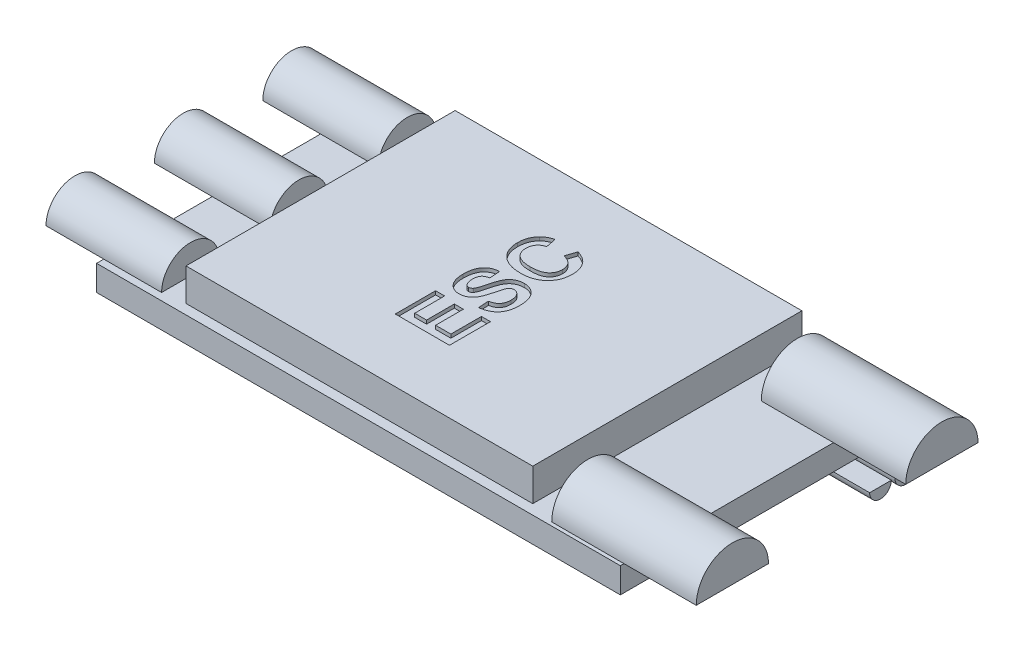
SolidWorks part; units mm, degrees
ref_plane "Front Plane" through (0, 0, 0) normal (0, 0, 1) x (1, 0, 0)
ref_plane "Top Plane" through (0, 0, 0) normal (0, 1, 0) x (1, 0, 0)
ref_plane "Right Plane" through (0, 0, 0) normal (1, 0, 0) x (0, 0, -1)
sketch "Sketch1" plane through (0, 0, 0) normal (0, 1, 0) x (1, 0, 0)
  line L1 (-14.5, 8) -> (14.5, 8)
  line L2 (-14.5, 8) -> (-14.5, -8)
  line L3 (-14.5, -8) -> (14.5, -8)
  line L4 (14.5, 8) -> (14.5, -8)
  line L5 (-14.5, 8) -> (14.5, -8) construction
  line L6 (-14.5, -8) -> (14.5, 8) construction
  point P0 (0, 0)
  dimension "D1" = 29
  dimension "D2" = 16
extrude "Boss-Extrude1" add sketch "Sketch1" along normal mid plane 1.4
sketch "Sketch2" plane through (0, 0.7, 0) normal (0, 1, 0) x (1, 0, 0)
  line L0 (-14.5, 0) -> (14.5, 0) construction
  line L1 (-14.5, 8) -> (-14.5, -8) construction
  line L2 (14.5, -8) -> (14.5, 8) construction
  line L4 (-10.1, 7.45) -> (9.1, 7.45)
  line L5 (-10.1, 7.45) -> (-10.1, -7.45)
  line L6 (-10.1, -7.45) -> (9.1, -7.45)
  line L7 (9.1, 7.45) -> (9.1, -7.45)
  line L8 (-10.1, 7.45) -> (9.1, -7.45) construction
  line L9 (-10.1, -7.45) -> (9.1, 7.45) construction
  point P6 (-0.5, 0)
  dimension "D1" = 14.9
  dimension "D2" = 19.2
  dimension "D3" = 5.4
extrude "Boss-Extrude2" add sketch "Sketch2" along normal blind 1.8
sketch "Sketch3" plane through (0, 0.7, 0) normal (0, 1, 0) x (1, 0, 0)
  line L0 (14.5, -5.8) -> (10.5, -5.8) construction
  line L1 (10.5, -3.8) -> (18.5, -3.8)
  line L2 (10.5, -3.8) -> (10.5, -7.8)
  line L3 (10.5, -7.8) -> (18.5, -7.8)
  line L4 (14.5, -8) -> (14.5, 8)
  line L5 (14.5, 8) -> (-14.5, 8)
  line L6 (-14.5, 8) -> (-14.5, -8)
  line L7 (-14.5, -8) -> (14.5, -8)
  line L8 (14.5, -8) -> (14.5, 8) construction
  line L9 (14.5, 8) -> (-14.5, 8) construction
  line L10 (-14.5, 8) -> (-14.5, -8) construction
  line L11 (-14.5, -8) -> (14.5, -8) construction
  line L12 (18.5, -3.8) -> (18.5, -7.8)
  line L13 (10.5, -3.8) -> (18.5, -7.8) construction
  line L14 (10.5, -7.8) -> (18.5, -3.8) construction
  line L15 (10.5, -5.8) -> (18.5, -5.8)
  point P2 (14.5, -5.8)
  dimension "D2" = 4
  dimension "D3" = 4
  dimension "D4" = 0.2
  dimension "D1" = 0
revolve "Revolve1" add sketch "Sketch3" angle 180 about L15
sketch "Sketch4" plane through (0, 0.7, 0) normal (0, 1, 0) x (1, 0, 0)
  line L0 (-17.7, 0) -> (-11.3, 0)
  line L1 (-17.7, 1.6) -> (-11.3, 1.6)
  line L2 (-17.7, 1.6) -> (-17.7, -1.6)
  line L3 (-17.7, -1.6) -> (-11.3, -1.6)
  line L4 (-11.3, 1.6) -> (-11.3, -1.6)
  line L5 (-17.7, 1.6) -> (-11.3, -1.6) construction
  line L6 (-17.7, -1.6) -> (-11.3, 1.6) construction
  line L13 (14.5, -3.8) -> (14.5, 8)
  line L14 (14.5, 8) -> (-14.5, 8)
  line L15 (-14.5, 8) -> (-14.5, -8)
  line L16 (-14.5, -8) -> (14.5, -8)
  line L17 (14.5, -8) -> (14.5, -7.8)
  line L18 (14.5, -7.8) -> (10.5, -7.8)
  line L19 (10.5, -7.8) -> (10.5, -3.8)
  line L20 (10.5, -3.8) -> (14.5, -3.8)
  line L25 (14.5, -3.8) -> (14.5, 8) construction
  line L26 (14.5, 8) -> (-14.5, 8) construction
  line L27 (-14.5, 8) -> (-14.5, -8) construction
  line L28 (-14.5, -8) -> (14.5, -8) construction
  line L29 (14.5, -8) -> (14.5, -7.8) construction
  line L30 (14.5, -7.8) -> (10.5, -7.8) construction
  line L31 (10.5, -7.8) -> (10.5, -3.8) construction
  line L32 (10.5, -3.8) -> (14.5, -3.8) construction
  point P2 (-14.5, 0)
  dimension "D2" = 3.2
  dimension "D3" = 3.2
  dimension "D1" = 0
revolve "Revolve2" add sketch "Sketch4" angle 180 about L0
sketch "Sketch5" plane through (0, 0.7, 0) normal (0, 1, 0) x (1, 0, 0)
  line L0 (-17.7, 0) -> (-11.3, 0) construction
  line L1 (-17.7, 0) -> (-11.3, 0) construction
  line L2 (-14.5, -1.6) -> (-14.5, -8) construction
  line L3 (-17.7, -4.4) -> (-11.3, -4.4)
  line L4 (-11.3, 1.6) -> (-17.7, 1.6)
  line L5 (-11.3, -1.6) -> (-11.3, 1.6)
  line L6 (-17.7, -1.6) -> (-11.3, -1.6)
  line L7 (-17.7, 1.6) -> (-17.7, -1.6)
  line L8 (-11.3, 1.6) -> (-17.7, 1.6) construction
  line L9 (-11.3, -1.6) -> (-11.3, 1.6) construction
  line L10 (-17.7, -1.6) -> (-11.3, -1.6) construction
  line L11 (-17.7, 1.6) -> (-17.7, -1.6) construction
  line L12 (-17.7, -4.4) -> (-17.7, -7.6)
  line L13 (-17.7, -7.6) -> (-11.3, -7.6)
  line L14 (-11.3, -4.4) -> (-11.3, -7.6)
  line L15 (-17.7, -4.4) -> (-11.3, -7.6) construction
  line L16 (-17.7, -7.6) -> (-11.3, -4.4) construction
  line L17 (-14.5, -8) -> (14.5, -8) construction
  line L18 (-17.7, -6) -> (-11.3, -6)
  point P6 (-14.5, -6)
  dimension "D2" = 3.2
  dimension "D3" = 3.2
  dimension "D4" = 0.4
  dimension "D1" = 0
revolve "Revolve3" add sketch "Sketch5" angle 180 about L18
mirror "Mirror1" about plane through (0, 0, 0) normal (0, 0, 1) of "Revolve3", "Revolve1"
sketch "Sketch6" plane through (0, -0.7, 0) normal (0, -1, 0) x (1, 0, 0)
  line L0 (12.5, -7.2) -> (16.5, -7.2)
  line L1 (12.5, -6.6) -> (16.5, -6.6)
  line L2 (12.5, -6.6) -> (12.5, -7.8)
  line L3 (12.5, -7.8) -> (16.5, -7.8)
  line L4 (14.5, -8) -> (14.5, 8)
  line L5 (14.5, 8) -> (-14.5, 8)
  line L6 (-14.5, 8) -> (-14.5, -8)
  line L7 (-14.5, -8) -> (14.5, -8)
  line L8 (14.5, -8) -> (14.5, 8) construction
  line L9 (14.5, 8) -> (-14.5, 8) construction
  line L10 (-14.5, 8) -> (-14.5, -8) construction
  line L11 (-14.5, -8) -> (14.5, -8) construction
  line L12 (16.5, -6.6) -> (16.5, -7.8)
  line L13 (12.5, -6.6) -> (16.5, -7.8) construction
  line L14 (12.5, -7.8) -> (16.5, -6.6) construction
  point P2 (14.5, -7.2)
  dimension "D2" = 2
  dimension "D3" = 1.2
  dimension "D4" = 0.2
  dimension "D1" = 0
revolve "Revolve4" add sketch "Sketch6" angle 180 about L0
pattern_linear "LPattern1" count 3 spacing 1.4 along (0, 0, 1) of "Revolve4"
sketch "Sketch7" plane through (0, 2.5, 0) normal (0, 1, 0) x (1, 0, 0)
  line L0 (-0.5, 7.45) -> (-0.5, -7.45) construction
  line L1 (1, 7.45) -> (1, -7.45) construction
  line L4 (9.1, -7.45) -> (9.1, 7.45)
  line L5 (9.1, 7.45) -> (-10.1, 7.45)
  line L6 (-10.1, 7.45) -> (-10.1, -7.45)
  line L7 (-10.1, -7.45) -> (9.1, -7.45)
  line L8 (9.1, -7.45) -> (9.1, 7.45) construction
  line L9 (9.1, 7.45) -> (-10.1, 7.45) construction
  line L10 (-10.1, 7.45) -> (-10.1, -7.45) construction
  line L11 (-10.1, -7.45) -> (9.1, -7.45) construction
  text T0 "ESC" font "Arial" height 3
  dimension "D1" = 0
  dimension "D2" = 1.5
extrude "Cut-Extrude1" cut sketch "Sketch7" against normal blind 0.2
sketch "Sketch8" plane through (0, 0, 0) normal (0, 1, 0) x (1, 0, 0)
  point P0 (0, 0)
